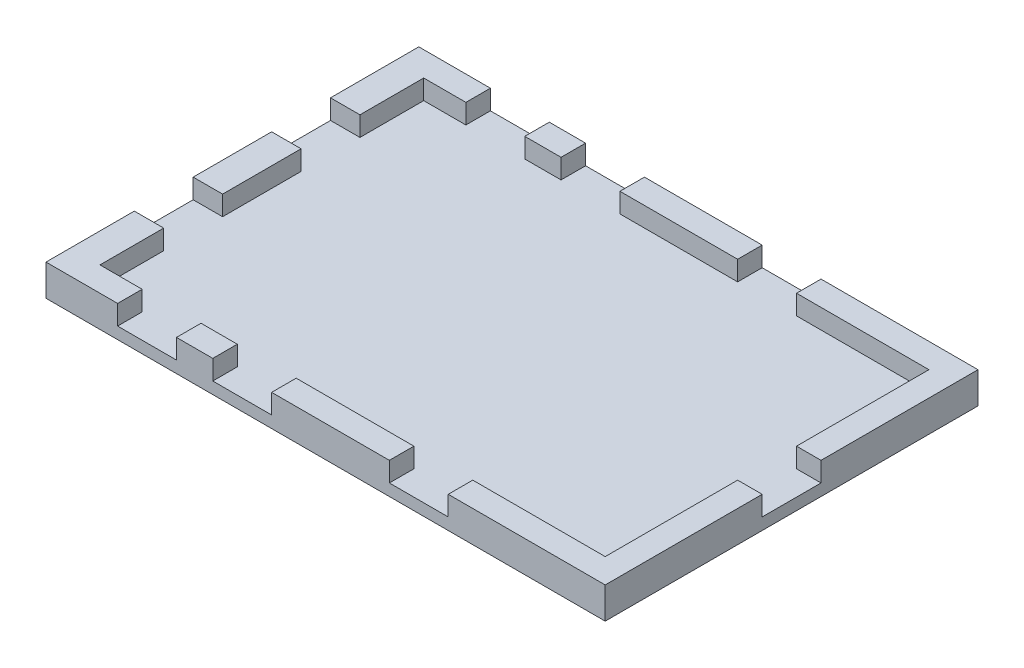
SolidWorks part; units mm, degrees
ref_plane "Front Plane" through (0, 0, 0) normal (0, 0, 1) x (1, 0, 0)
ref_plane "Top Plane" through (0, 0, 0) normal (0, 1, 0) x (1, 0, 0)
ref_plane "Right Plane" through (0, 0, 0) normal (1, 0, 0) x (0, 0, -1)
sketch "Sketch1" plane through (0, 0, 0) normal (0, 1, 0) x (1, 0, 0)
  line L0 (-27, -19) -> (-30, -19)
  line L1 (-27, -19) -> (27, -19)
  line L2 (-27, -19) -> (-27, 19)
  line L3 (-27, 19) -> (27, 19)
  line L4 (27, -19) -> (27, 19)
  line L5 (-27, -19) -> (27, 19) construction
  line L6 (-27, 19) -> (27, -19) construction
  line L7 (-30, -19) -> (-30, 19)
  line L8 (-30, 19) -> (-27, 19)
  point P0 (0, 0)
  dimension "D1" = 54
  dimension "D2" = 38
  dimension "D3" = 3
extrude "Boss-Extrude1" add sketch "Sketch1" along normal blind 1.2 contours L8 L7 L0 L2
sketch "Sketch3" plane through (0, 1.2, 0) normal (0, 1, 0) x (1, 0, 0)
  line L0 (-27, -19) -> (27, -19)
  line L1 (27, -19) -> (27, 19)
  line L2 (27, 19) -> (-27, 19)
  line L3 (-27, 19) -> (-27, 16.5)
  line L4 (-27, 16.5) -> (24.5, 16.5)
  line L5 (24.5, 16.5) -> (24.5, -16.5)
  line L6 (24.5, -16.5) -> (-27, -16.5)
  line L7 (-27, -16.5) -> (-27, -19)
  line L8 (-22.7, 16.5) -> (-22.7, 19)
  line L9 (-16.7, 16.5) -> (-16.7, 19)
  line L10 (-13, 16.5) -> (-13, 19)
  line L11 (-7, 16.5) -> (-7, 19)
  line L12 (5, 16.5) -> (5, 19)
  line L13 (11, 16.5) -> (11, 19)
  line L14 (24.5, 3) -> (27, 3)
  line L15 (24.5, -3) -> (27, -3)
  line L16 (-30, 0) -> (27, 0) construction
  line L18 (11, -16.5) -> (11, -19)
  line L19 (5, -19) -> (5, -16.5)
  line L20 (-7, -16.5) -> (-7, -19)
  line L21 (-13, -16.5) -> (-13, -19)
  line L22 (-16.7, -16.5) -> (-16.7, -19)
  line L23 (-22.7, -16.5) -> (-22.7, -19)
  line L24 (-27, -19) -> (-30, -19)
  line L25 (-27, -16.5) -> (-27, 16.5)
  line L26 (-30, -19) -> (-30, 19)
  line L27 (-30, 19) -> (-27, 19)
  line L28 (-27, 16.5) -> (-27, -16.5)
  line L29 (-27, -10) -> (-30, -10)
  line L30 (-27, 16.5) -> (-27, -16.5)
  line L31 (-27, -4) -> (-30, -4)
  line L32 (-27, 4) -> (-30, 4)
  line L33 (-27, 10) -> (-30, 10)
  line L34 (-30, -19) -> (-30, 19) construction
  point P2 (27, 0)
  point P5 (0, -19)
  point P13 (24.5, 0)
  point P30 (-30, 0)
  dimension "D1" = 38
  dimension "D2" = 54
  dimension "D3" = 33
  dimension "D4" = 51.5
  dimension "D5" = 6
  dimension "D6" = 6
  dimension "D7" = 4.3
  dimension "D8" = 20
  dimension "D9" = 6
  dimension "D10" = 13.5
  dimension "D11" = 6
  dimension "D12" = 6.5
  dimension "D13" = 6
  dimension "D14" = 6
  dimension "D15" = 3
extrude "Boss-Extrude2" add sketch "Sketch3" along normal blind 2
